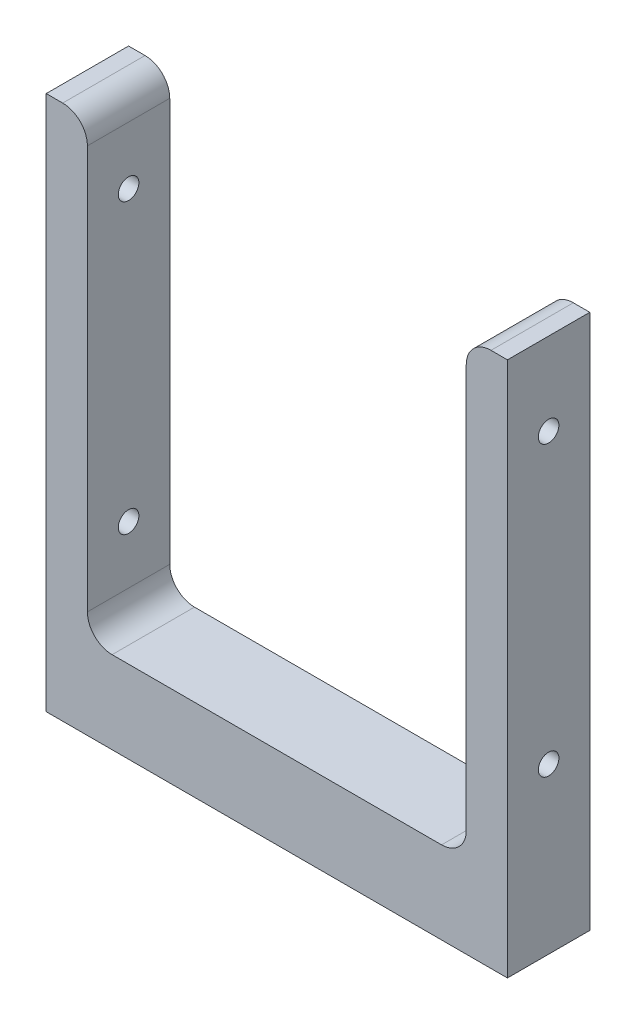
SolidWorks part; units mm, degrees
ref_plane "Спереди" through (0, 0, 0) normal (0, 0, 1) x (1, 0, 0)
ref_plane "Сверху" through (0, 0, 0) normal (0, 1, 0) x (1, 0, 0)
ref_plane "Справа" through (0, 0, 0) normal (1, 0, 0) x (0, 0, -1)
sketch "Эскиз1" plane through (0, 0, 0) normal (0, 0, 1) x (1, 0, 0)
  line L0 (28, 32.5) -> (23, 32.5)
  line L1 (-28, 32.5) -> (-23, 32.5)
  line L2 (-28, 32.5) -> (-28, -32.5)
  line L3 (-28, -32.5) -> (28, -32.5)
  line L4 (28, 32.5) -> (28, -32.5)
  line L5 (-28, 32.5) -> (28, -32.5) construction
  line L6 (-28, -32.5) -> (28, 32.5) construction
  line L7 (23, 32.5) -> (23, -22.5)
  line L8 (-23, -22.5) -> (23, -22.5)
  line L9 (-23, 32.5) -> (-23, -22.5)
  point P0 (0, 0)
  dimension "D1" = 56
  dimension "D2" = 65
  dimension "D3" = 5
  dimension "D4" = 10
  dimension "D5" = 5
extrude "Бобышка-Вытянуть1" add sketch "Эскиз1" along normal blind 10
fillet "Скругление1" radius 3 4 edges at (23, -22.5, 5) (-23, -22.5, 5) (-23, 32.5, 5) (23, 32.5, 5)
sketch "Эскиз2" plane through (0, -32.5, 0) normal (0, -1, 0) x (1, 0, 0)
  line L0 (-28, 5) -> (28, 5) construction
  line L1 (-28, 10) -> (-28, 0) construction
  line L2 (28, 10) -> (28, 0) construction
  line L3 (-18, 10) -> (-18, 0) construction
  line L4 (-28, 10) -> (28, 10) construction
  line L5 (-28, 0) -> (28, 0) construction
  line L6 (18, 10) -> (18, 0) construction
  dimension "D1" = 10
  dimension "D2" = 10
hole_wizard "Отверстие обработанное метчиком M3x0.51" [suppressed] positions "Эскиз4" profile "Эскиз3" tap size "M3x0.5" standard "Ansi Metric"
sketch "Эскиз4" plane through (0, -32.5, 0) normal (0, -1, 0) x (-1, 0, 0)
  line L0 (18, -10) -> (18, 0) construction
  line L1 (-18, -10) -> (-18, 0) construction
  point P0 (18, -5)
  point P4 (-18, -5)
sketch "Эскиз3" plane through (-18, -32.5, 5) normal (1, 0, 0) x (0, 0, -1)
  line L0 (0, 0) -> (0, 65)
  line L1 (0, 65) -> (1.25, 65)
  line L2 (1.25, 65) -> (1.25, 0)
  line L5 (1.25, 0) -> (0, 0)
  line L11 (0, -6.35) -> (0, 107.95) construction
  dimension "Диаметр проходного сверла" = 2.5
  dimension "Глубина проходного сверла" = 65
cosmetic thread "Отверстие резьбы1" [suppressed] parameters "D2"=3
cosmetic thread "Отверстие резьбы2" [suppressed] parameters "D2"=3
sketch "Эскиз5" plane through (28, 0, 0) normal (1, 0, 0) x (0, 0, -1)
  line L0 (-5, 32.5) -> (-5, -32.5) construction
  line L1 (-10, 32.5) -> (0, 32.5) construction
  line L2 (-10, -32.5) -> (0, -32.5) construction
  line L3 (-6.8609, 22.5) -> (-1.9029, 22.5) construction
  line L4 (-2.7189, -12.5) -> (-7.8192, -12.5) construction
  dimension "D1" = 20
  dimension "D2" = 10
hole_wizard "Отверстие обработанное метчиком M3x0.52" positions "Эскиз7" profile "Эскиз6" tap size "M3x0.5" standard "Ansi Metric" end condition through all
sketch "Эскиз7" plane through (28, 0, 0) normal (1, 0, 0) x (0, 0, -1)
  line L0 (-5, 32.5) -> (-5, -32.5) construction
  line L1 (-6.8609, 22.5) -> (-1.9029, 22.5) construction
  line L2 (-2.7189, -12.5) -> (-7.8192, -12.5) construction
  point P0 (-5, 22.5)
  point P6 (-5, -12.5)
sketch "Эскиз6" plane through (28, 22.5, 5) normal (0, 1, 0) x (0, 0, -1)
  line L0 (0, 0) -> (0, 56)
  line L1 (0, 56) -> (1.25, 56)
  line L2 (1.25, 56) -> (1.25, 0)
  line L5 (1.25, 0) -> (0, 0)
  line L11 (0, -6.35) -> (0, 107.95) construction
  dimension "Диаметр проходного сверла" = 2.5
  dimension "Глубина проходного сверла" = 56
cosmetic thread "Отверстие резьбы3" parameters "D2"=3
cosmetic thread "Отверстие резьбы4" parameters "D2"=3
